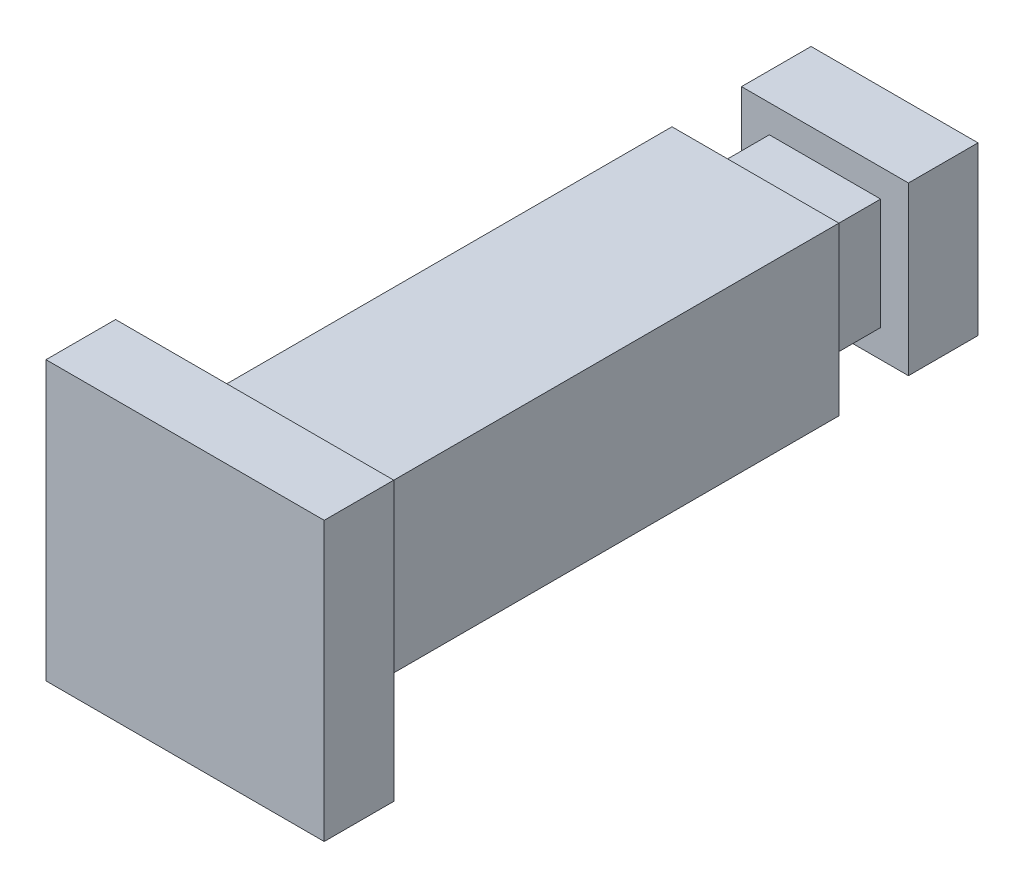
SolidWorks part; units mm, degrees
ref_plane "Front Plane" through (0, 0, 0) normal (0, 0, 1) x (1, 0, 0)
ref_plane "Top Plane" through (0, 0, 0) normal (0, 1, 0) x (1, 0, 0)
ref_plane "Right Plane" through (0, 0, 0) normal (1, 0, 0) x (0, 0, -1)
sketch "Sketch1" plane through (0, 0, 0) normal (0, 0, 1) x (1, 0, 0)
  line L1 (0, 0) -> (6, 0)
  line L2 (0, 0) -> (0, 6)
  line L3 (0, 6) -> (6, 6)
  line L4 (6, 0) -> (6, 6)
  dimension "D1" = 6
  dimension "D2" = 6
extrude "Boss-Extrude1" add sketch "Sketch1" along normal blind 18 contours L2 L3 L4 L1
sketch "Sketch2" plane through (0, 0, 18) normal (0, 0, 1) x (1, 0, 0)
  line L0 (0, 6) -> (6, 6) construction
  line L1 (-2, 8) -> (8, 8)
  line L2 (-2, 8) -> (-2, -2)
  line L3 (-2, -2) -> (8, -2)
  line L4 (8, 8) -> (8, -2)
  line L5 (0, 0) -> (0, 6) construction
  point P4 (3, 8)
  point P7 (3, 6)
  point P8 (-2, 3)
  point P11 (0, 3)
  dimension "D1" = 0
  dimension "D2" = 0
  dimension "D3" = 10
  dimension "D4" = 10
extrude "Boss-Extrude2" add sketch "Sketch2" along normal blind 2.5
sketch "Sketch5" plane through (0, 0, 0) normal (0, 0, -1) x (-1, 0, 0)
  line L0 (0, 6) -> (-6, 6) construction
  line L1 (-5, 5) -> (-1, 5)
  line L2 (-5, 5) -> (-5, 1)
  line L3 (-5, 1) -> (-1, 1)
  line L4 (-1, 5) -> (-1, 1)
  line L5 (-6, 0) -> (-6, 6) construction
  point P4 (-3, 5)
  point P7 (-3, 6)
  point P8 (-5, 3)
  point P11 (-6, 3)
  dimension "D1" = 0
  dimension "D2" = 0
  dimension "D3" = 4
  dimension "D4" = 4
extrude "Boss-Extrude4" add sketch "Sketch5" along normal blind 2.5
sketch "Sketch6" plane through (0, 0, -2.5) normal (0, 0, -1) x (-1, 0, 0)
  line L1 (-6, 6) -> (0, 6)
  line L2 (-6, 6) -> (-6, 0)
  line L3 (-6, 0) -> (0, 0)
  line L4 (0, 6) -> (0, 0)
extrude "Boss-Extrude5" add sketch "Sketch6" along normal blind 2.5
